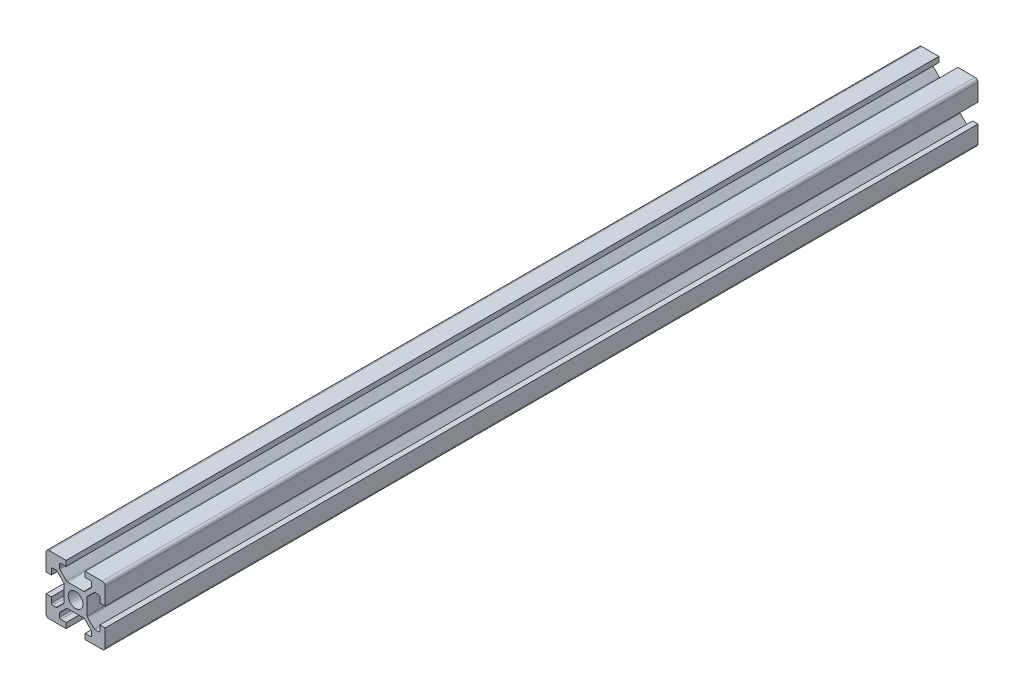
SolidWorks part; units mm, degrees
material "1060 Alloy"
ref_plane "Front Plane" through (0, 0, 0) normal (0, 0, 1) x (1, 0, 0)
ref_plane "Top Plane" through (0, 0, 0) normal (0, 1, 0) x (1, 0, 0)
ref_plane "Right Plane" through (0, 0, 0) normal (1, 0, 0) x (0, 0, -1)
sketch "Sketch1" plane through (0, 0, 0) normal (0, 0, 1) x (1, 0, 0)
  line L0 (20, 0) -> (-8.059, 28.059) construction
  line L1 (0, 0) -> (6.8, 0)
  line L2 (0, 0) -> (0, 6.8)
  line L3 (0, 20) -> (6.8, 20)
  line L4 (20, 0) -> (20, 6.8)
  line L5 (6.8, 20) -> (6.8, 18.2)
  line L6 (20, 20) -> (8.2322, 8.2322) construction
  line L7 (12.95, 6.1) -> (7.05, 6.1)
  line L8 (13.9, 7.05) -> (13.9, 12.95)
  line L9 (12.95, 13.9) -> (7.05, 13.9)
  line L10 (6.1, 7.05) -> (6.1, 12.95)
  line L11 (13.9, 6.1) -> (6.1, 13.9) construction
  line L12 (13.9, 13.9) -> (6.1, 6.1) construction
  line L13 (4.55, 16.4) -> (7.05, 13.9)
  line L14 (13.2, 18.2) -> (13.2, 20)
  line L15 (1.8, 6.8) -> (0, 6.8)
  line L16 (0, 13.2) -> (0, 20)
  line L17 (0, 13.2) -> (1.8, 13.2)
  line L18 (10, 10) -> (10, 13.9) construction
  line L19 (16.4, 4.55) -> (13.9, 7.05)
  line L20 (4.55, 16.4) -> (4.55, 18.2)
  line L21 (4.55, 18.2) -> (6.8, 18.2)
  line L22 (13.2, 18.2) -> (15.45, 18.2)
  line L23 (15.45, 18.2) -> (15.45, 16.4)
  line L24 (15.45, 16.4) -> (12.95, 13.9)
  line L25 (16.4, 4.55) -> (18.2, 4.55)
  line L26 (18.2, 4.55) -> (18.2, 6.8)
  line L27 (20, 6.8) -> (18.2, 6.8)
  line L28 (18.2, 13.2) -> (20, 13.2)
  line L29 (18.2, 13.2) -> (18.2, 15.45)
  line L30 (18.2, 15.45) -> (16.4, 15.45)
  line L31 (16.4, 15.45) -> (13.9, 12.95)
  line L32 (1.8, 4.55) -> (3.6, 4.55)
  line L33 (3.6, 15.45) -> (6.1, 12.95)
  line L34 (3.6, 15.45) -> (1.8, 15.45)
  line L35 (1.8, 15.45) -> (1.8, 13.2)
  line L36 (0, 13.2) -> (1.8, 13.2)
  line L37 (1.8, 6.8) -> (0, 6.8)
  line L38 (3.6, 4.55) -> (6.1, 7.05)
  line L39 (1.8, 6.8) -> (1.8, 4.55)
  line L40 (15.45, 3.6) -> (12.95, 6.1)
  line L41 (4.55, 3.6) -> (7.05, 6.1)
  line L42 (4.55, 1.8) -> (4.55, 3.6)
  line L43 (6.8, 1.8) -> (4.55, 1.8)
  line L44 (6.8, 1.8) -> (6.8, 0)
  line L45 (15.45, 3.6) -> (15.45, 1.8)
  line L46 (15.45, 1.8) -> (13.2, 1.8)
  line L47 (13.2, 0) -> (13.2, 1.8)
  line L48 (13.2, 20) -> (20, 20)
  line L49 (20, 13.2) -> (20, 20)
  line L50 (13.2, 0) -> (20, 0)
  line L51 (6.1, 6.1) -> (-5.5045, -5.5045) construction
  circle A0 centre (10, 10) radius 2.5
  point P25 (10, 16.4)
  point P39 (13.2, 19.1)
  point P46 (0.9, 6.8)
  dimension "D3" = 5
  dimension "D2" = 20
  dimension "D4" = 7.8
  dimension "D5" = 7.8
  dimension "D6" = 6.8
  dimension "D7" = 6.8
  dimension "D8" = 1.8
  dimension "D9" = 10.9
  dimension "D10" = 1.8
  dimension "D11" = 10.9
  dimension "D12" = 20
extrude "Boss-Extrude1" add sketch "Sketch1" along normal blind 295 contours L47 L50 L4 L27 L26 L25 L19 L8 L31 L30 L29 L28 L49 L48 L14 L22 L23 L24 L9 L13 L20 L21 L5 L3 L16 L17 L35 L34 L33 L10 L38 L32 L39 L15 L2 L1 L44 L43 L42 L41 L7 L40 L45 L46 A0
fillet "Fillet1" radius 1 4 edges at (20, 20, 147.5) (20, 0, 147.5) (0, 0, 147.5) (0, 20, 147.5)
fillet "Fillet2" radius 0.5 6 edges at (4.55, 18.2, 147.5) (4.55, 16.4, 147.5) (7.05, 13.9, 147.5) (15.45, 18.2, 147.5) (15.45, 16.4, 147.5) (12.95, 13.9, 147.5)
fillet "Fillet3" radius 0.5 6 edges at (18.2, 15.45, 147.5) (16.4, 15.45, 147.5) (13.9, 12.95, 147.5) (18.2, 4.55, 147.5) (13.9, 7.05, 147.5) (16.4, 4.55, 147.5)
fillet "Fillet4" radius 0.5 6 edges at (1.8, 15.45, 147.5) (3.6, 15.45, 147.5) (6.1, 12.95, 147.5) (3.6, 4.55, 147.5) (1.8, 4.55, 147.5) (6.1, 7.05, 147.5)
fillet "Fillet5" radius 0.5 6 edges at (7.05, 6.1, 147.5) (4.55, 3.6, 147.5) (4.55, 1.8, 147.5) (15.45, 1.8, 147.5) (15.45, 3.6, 147.5) (12.95, 6.1, 147.5)
